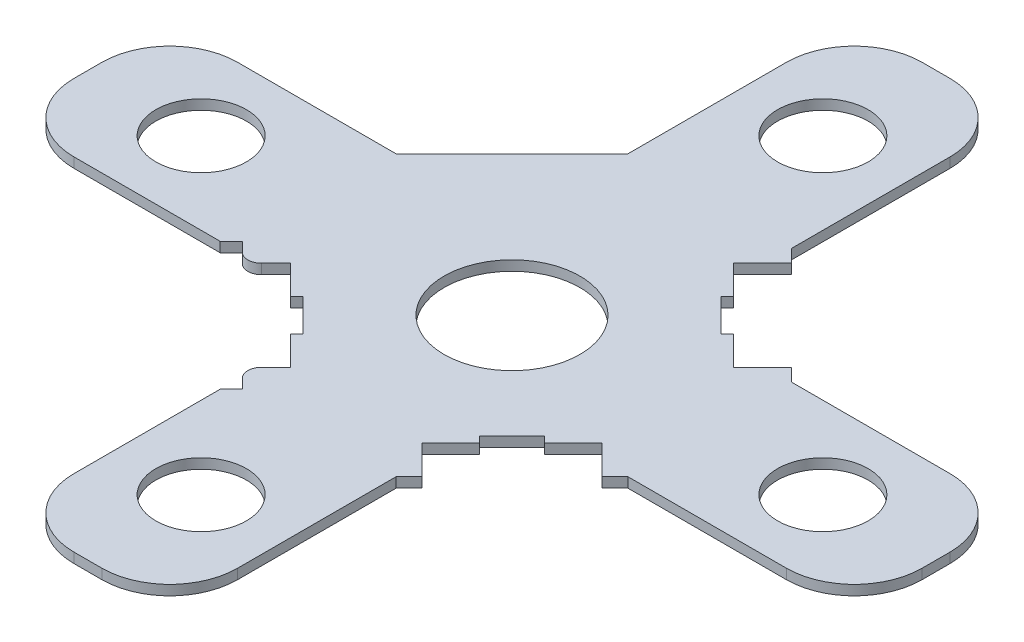
SolidWorks part; units mm, degrees
material "cardboard"
ref_plane "Front Plane" through (0, 0, 0) normal (0, 0, 1) x (1, 0, 0)
ref_plane "Top Plane" through (0, 0, 0) normal (0, 1, 0) x (1, 0, 0)
ref_plane "Right Plane" through (0, 0, 0) normal (1, 0, 0) x (0, 0, -1)
sketch "Sketch1" plane through (0, 0, 0) normal (0, 1, 0) x (1, 0, 0)
  line L0 (-130.5636, 127.4376) -> (-119.5636, 127.4376)
  line L1 (-120.5636, 123.4376) -> (-120.5636, 107.4376)
  line L2 (-60.7636, 123.4376) -> (-60.7636, 107.4376)
  line L3 (-118.1636, 107.4376) -> (-120.5636, 107.4376)
  line L4 (-131.9636, 123.4376) -> (-129.5636, 123.4376)
  line L5 (-131.9636, 123.4376) -> (-131.9636, 107.4376)
  line L6 (-131.9636, 107.4376) -> (-129.5636, 107.4376)
  line L7 (-129.5636, 123.4376) -> (-129.5636, 107.4376)
  line L8 (-118.1636, 123.4376) -> (-118.1636, 107.4376)
  line L9 (-118.1636, 123.4376) -> (-120.5636, 123.4376)
  line L10 (-58.3636, 123.4376) -> (-58.3636, 107.4376)
  line L11 (-94.9636, 127.4376) -> (-83.9636, 127.4376)
  line L12 (-60.7636, 123.4376) -> (-58.3636, 123.4376)
  line L13 (-60.7636, 107.4376) -> (-58.3636, 107.4376)
  line L14 (-49.3636, 123.4376) -> (-49.3636, 107.4376)
  line L15 (-46.9636, 123.4376) -> (-49.3636, 123.4376)
  line L16 (-46.9636, 123.4376) -> (-46.9636, 107.4376)
  line L17 (-46.9636, 107.4376) -> (-49.3636, 107.4376)
  line L18 (10.4364, 123.4376) -> (10.4364, 107.4376)
  line L19 (12.8364, 123.4376) -> (12.8364, 107.4376)
  line L20 (10.4364, 123.4376) -> (12.8364, 123.4376)
  line L21 (10.4364, 107.4376) -> (12.8364, 107.4376)
  line L22 (21.8364, 123.4376) -> (21.8364, 107.4376)
  line L23 (24.2364, 123.4376) -> (21.8364, 123.4376)
  line L24 (24.2364, 123.4376) -> (24.2364, 107.4376)
  line L25 (24.2364, 107.4376) -> (21.8364, 107.4376)
  line L26 (81.6364, 123.4376) -> (81.6364, 107.4376)
  line L27 (84.0364, 123.4376) -> (84.0364, 107.4376)
  line L28 (-59.3636, 127.4376) -> (-48.3636, 127.4376)
  line L29 (81.6364, 123.4376) -> (84.0364, 123.4376)
  line L30 (81.6364, 107.4376) -> (84.0364, 107.4376)
  line L31 (93.0364, 123.4376) -> (93.0364, 107.4376)
  line L32 (58.4364, 129.4376) -> (83.0364, 129.4376)
  line L33 (95.4364, 123.4376) -> (93.0364, 123.4376)
  line L34 (95.4364, 123.4376) -> (95.4364, 107.4376)
  line L35 (95.4364, 107.4376) -> (93.0364, 107.4376)
  line L36 (64.4935, 37.401) -> (70.9093, 30.9852)
  line L37 (84.3963, 17.4982) -> (86.3761, 19.4781)
  line L38 (64.4935, 37.401) -> (66.4734, 39.3809)
  line L39 (77.9804, 23.9141) -> (84.3963, 17.4982)
  line L40 (84.3963, -85.3527) -> (77.9804, -91.7686)
  line L41 (84.3963, -85.3527) -> (86.3761, -87.3326)
  line L42 (86.3761, -87.3326) -> (66.4734, -107.2354)
  line L43 (64.4935, -105.2555) -> (66.4734, -107.2354)
  line L44 (70.9093, -98.8396) -> (64.4935, -105.2555)
  line L45 (-38.3575, -105.2555) -> (-44.7733, -98.8396)
  line L46 (-38.3575, -105.2555) -> (-40.3374, -107.2354)
  line L47 (-40.3374, -107.2354) -> (-60.2402, -87.3326)
  line L48 (-58.2603, -85.3527) -> (-60.2402, -87.3326)
  line L49 (-51.8444, -91.7686) -> (-58.2603, -85.3527)
  line L50 (-23.7636, 127.4376) -> (-12.7636, 127.4376)
  line L51 (11.8364, 127.4376) -> (22.8364, 127.4376)
  line L52 (47.4364, 127.4376) -> (58.4364, 127.4376)
  line L53 (83.0364, 127.4376) -> (94.0364, 127.4376)
  line L54 (118.6364, 127.4376) -> (129.6364, 127.4376)
  line L55 (-35.0341, -101.9321) -> (-32.9647, -104.0015)
  line L56 (-4.6285, -75.7691) -> (-2.5591, -77.8386)
  line L57 (-54.9369, -82.0293) -> (-56.7046, -83.7971)
  line L58 (-35.0341, -101.9321) -> (-36.8019, -103.6999)
  line L59 (-30.8433, -49.5543) -> (-57.0063, -75.7172)
  line L60 (-57.0063, -79.9599) -> (-54.9369, -82.0293)
  line L61 (-2.5591, -77.8386) -> (-28.722, -104.0015)
  line L62 (-30.8433, -49.5543) -> (-28.7739, -51.6237)
  line L63 (-142.8636, 129.4376) -> (-130.5636, 129.4376)
  line L64 (-54.2479, 82.1393) -> (-54.2479, 87.1393)
  line L65 (-64.2479, 82.1393) -> (-64.2479, 87.1393)
  line L66 (-33.698, 73.6273) -> (-30.1625, 77.1628)
  line L67 (-26.627, 66.5562) -> (-23.0914, 70.0917)
  line L68 (-18.1149, 46.0063) -> (-13.1149, 46.0063)
  line L69 (-18.1149, 36.0063) -> (-13.1149, 36.0063)
  line L70 (-26.627, 15.4564) -> (-23.0914, 11.9208)
  line L71 (-33.698, 8.3853) -> (-30.1625, 4.8498)
  line L72 (-54.2479, -0.1268) -> (-54.2479, -5.1268)
  line L73 (-64.2479, -0.1268) -> (-64.2479, -5.1268)
  line L74 (-84.7978, 8.3853) -> (-88.3334, 4.8498)
  line L75 (62.9378, 35.8454) -> (69.3537, 29.4295)
  line L76 (76.4248, 22.3585) -> (82.8406, 15.9426)
  line L77 (76.4248, 22.3585) -> (77.9804, 23.9141)
  line L78 (69.3537, 29.4295) -> (70.9093, 30.9852)
  line L79 (31.1414, -77.5603) -> (33.9698, -74.7318)
  line L80 (56.701, -15.8538) -> (53.8726, -13.0254)
  line L81 (-142.8636, 129.4376) -> (-142.8636, 119.4376)
  line L82 (-5.0054, 9.7058) -> (-30.565, -15.8538)
  line L83 (-142.8636, 101.4376) -> (-127.0636, 101.4376)
  line L84 (-91.8689, 15.4564) -> (-95.4044, 11.9208)
  line L85 (-107.2636, 120.4376) -> (-107.2636, 110.4376)
  line L86 (66.4734, 39.3809) -> (86.3761, 19.4781)
  line L87 (-21.3493, -48.4417) -> (-1.4465, -68.3445)
  line L88 (-21.3493, -48.4417) -> (-24.5313, -51.6237)
  line L89 (-1.4465, -68.3445) -> (-4.6285, -71.5265)
  line L90 (-30.565, -15.8538) -> (-65.565, -15.8538)
  line L91 (-80.565, -30.8538) -> (-80.565, -37.0006)
  line L92 (-65.565, -52.0006) -> (-33.2897, -52.0006)
  line L93 (-110.5636, 106.4376) -> (-113.0636, 106.4376)
  line L94 (-139.5636, 126.4376) -> (-137.0636, 126.4376)
  line L95 (-139.5636, 126.4376) -> (-139.5636, 106.4376)
  line L96 (-139.5636, 106.4376) -> (-137.0636, 106.4376)
  line L97 (-137.0636, 126.4376) -> (-137.0636, 106.4376)
  line L98 (-113.0636, 126.4376) -> (-113.0636, 106.4376)
  line L99 (31.1414, 9.7058) -> (31.1414, 44.7058)
  line L100 (16.1414, 59.7058) -> (9.9946, 59.7058)
  line L101 (-5.0054, 44.7058) -> (-5.0054, 9.7058)
  line L102 (-110.5636, 126.4376) -> (-113.0636, 126.4376)
  line L103 (-110.5636, 126.4376) -> (-110.5636, 106.4376)
  line L104 (-123.0636, 101.4376) -> (-108.7636, 101.4376)
  line L105 (-107.2636, 120.4376) -> (-107.2636, 110.4376)
  line L106 (56.701, -52.0006) -> (91.701, -52.0006)
  line L107 (106.701, -37.0006) -> (106.701, -30.8538)
  line L108 (91.701, -15.8538) -> (56.701, -15.8538)
  line L109 (-73.1636, 101.4376) -> (-71.6636, 101.4376)
  line L110 (-71.6636, 129.4376) -> (-71.6636, 101.4376)
  line L111 (22.8364, 129.4376) -> (47.4364, 129.4376)
  line L112 (-71.6636, 129.4376) -> (-71.6636, 101.4376)
  line L113 (-71.6636, 101.4376) -> (-36.0636, 101.4376)
  line L114 (-36.0636, 129.4376) -> (-36.0636, 101.4376)
  line L115 (-5.0054, -80.2849) -> (-5.0054, -112.5603)
  line L116 (9.9946, -127.5603) -> (16.1414, -127.5603)
  line L117 (31.1414, -112.5603) -> (31.1414, -77.5603)
  line L118 (-12.7636, 129.4376) -> (11.8364, 129.4376)
  line L119 (-36.0636, 129.4376) -> (-36.0636, 101.4376)
  line L120 (-36.0636, 101.4376) -> (-0.4636, 101.4376)
  line L121 (-0.4636, 129.4376) -> (-0.4636, 101.4376)
  line L122 (-48.3636, 129.4376) -> (-23.7636, 129.4376)
  line L123 (-0.4636, 129.4376) -> (-0.4636, 101.4376)
  line L124 (53.8726, -54.8291) -> (56.701, -52.0006)
  line L125 (27.5825, -68.3445) -> (47.4853, -48.4417)
  line L126 (82.8406, -83.7971) -> (76.4248, -90.2129)
  line L127 (47.4853, -48.4417) -> (82.8406, -83.7971)
  line L128 (76.4248, -90.2129) -> (77.9804, -91.7686)
  line L129 (79.9603, -93.7485) -> (72.8892, -100.8195)
  line L130 (27.5825, -68.3445) -> (62.9378, -103.6999)
  line L131 (69.3537, -97.284) -> (70.9093, -98.8396)
  line L132 (69.3537, -97.284) -> (62.9378, -103.6999)
  line L133 (-36.8019, -103.6999) -> (-43.2177, -97.284)
  line L134 (-43.2177, -97.284) -> (-44.7733, -98.8396)
  line L135 (33.9698, 6.8774) -> (31.1414, 9.7058)
  line L136 (-100.381, 36.0063) -> (-105.381, 36.0063)
  line L137 (47.4853, -19.4127) -> (27.5825, 0.4901)
  line L138 (47.4853, -19.4127) -> (82.8406, 15.9426)
  line L139 (27.5825, 0.4901) -> (62.9378, 35.8454)
  line L140 (-46.7532, -100.8195) -> (-53.8243, -93.7485)
  line L141 (-50.2888, -90.2129) -> (-51.8444, -91.7686)
  line L142 (-50.2888, -90.2129) -> (-56.7046, -83.7971)
  line L143 (-64.2479, 82.1393) -> (-76.2858, 82.1393)
  line L144 (-76.2858, 82.1393) -> (-84.7978, 73.6273)
  line L145 (-0.4636, 101.4376) -> (35.1364, 101.4376)
  line L146 (35.1364, 129.4376) -> (35.1364, 101.4376)
  line L147 (-83.9636, 129.4376) -> (-59.3636, 129.4376)
  line L148 (35.1364, 129.4376) -> (35.1364, 101.4376)
  line L149 (35.1364, 101.4376) -> (70.7364, 101.4376)
  line L150 (70.7364, 129.4376) -> (70.7364, 101.4376)
  line L151 (-119.5636, 129.4376) -> (-108.7636, 129.4376)
  line L152 (70.7364, 129.4376) -> (70.7364, 101.4376)
  line L153 (70.7364, 101.4376) -> (106.3364, 101.4376)
  line L154 (106.3364, 129.4376) -> (106.3364, 101.4376)
  line L155 (129.6364, 129.4376) -> (141.9364, 129.4376)
  line L156 (106.3364, 129.4376) -> (106.3364, 101.4376)
  line L157 (106.3364, 101.4376) -> (141.9364, 101.4376)
  line L158 (141.9364, 129.4376) -> (141.9364, 119.4376)
  line L159 (-68.3636, 126.4376) -> (-65.8636, 126.4376)
  line L160 (-68.3636, 126.4376) -> (-68.3636, 106.4376)
  line L161 (-68.3636, 106.4376) -> (-65.8636, 106.4376)
  line L162 (-65.8636, 126.4376) -> (-65.8636, 106.4376)
  line L163 (-41.8636, 126.4376) -> (-41.8636, 106.4376)
  line L164 (-39.3636, 106.4376) -> (-41.8636, 106.4376)
  line L165 (-39.3636, 126.4376) -> (-39.3636, 106.4376)
  line L166 (-39.3636, 126.4376) -> (-41.8636, 126.4376)
  line L167 (-59.8636, 101.4376) -> (-59.8636, 97.4376)
  line L168 (-59.8636, 97.4376) -> (-47.8636, 97.4376)
  line L169 (-47.8636, 97.4376) -> (-47.8636, 101.4376)
  line L170 (2.8364, 126.4376) -> (5.3364, 126.4376)
  line L171 (2.8364, 126.4376) -> (2.8364, 106.4376)
  line L172 (2.8364, 106.4376) -> (5.3364, 106.4376)
  line L173 (5.3364, 126.4376) -> (5.3364, 106.4376)
  line L174 (29.3364, 126.4376) -> (29.3364, 106.4376)
  line L175 (31.8364, 106.4376) -> (29.3364, 106.4376)
  line L176 (31.8364, 126.4376) -> (31.8364, 106.4376)
  line L177 (31.8364, 126.4376) -> (29.3364, 126.4376)
  line L178 (11.3364, 101.4376) -> (11.3364, 97.4376)
  line L179 (11.3364, 97.4376) -> (23.3364, 97.4376)
  line L180 (23.3364, 97.4376) -> (23.3364, 101.4376)
  line L181 (74.0364, 126.4376) -> (76.5364, 126.4376)
  line L182 (74.0364, 126.4376) -> (74.0364, 106.4376)
  line L183 (74.0364, 106.4376) -> (76.5364, 106.4376)
  line L184 (76.5364, 126.4376) -> (76.5364, 106.4376)
  line L185 (100.5364, 126.4376) -> (100.5364, 106.4376)
  line L186 (103.0364, 106.4376) -> (100.5364, 106.4376)
  line L187 (103.0364, 126.4376) -> (103.0364, 106.4376)
  line L188 (103.0364, 126.4376) -> (100.5364, 126.4376)
  line L189 (82.5364, 101.4376) -> (82.5364, 97.4376)
  line L190 (82.5364, 97.4376) -> (94.5364, 97.4376)
  line L191 (94.5364, 97.4376) -> (94.5364, 101.4376)
  line L192 (-127.0636, 101.4376) -> (-127.0636, 102.4376)
  line L193 (-127.0636, 102.4376) -> (-123.0636, 102.4376)
  line L194 (-123.0636, 102.4376) -> (-123.0636, 101.4376)
  line L195 (-59.8636, 100.4376) -> (-55.8636, 100.4376)
  line L196 (-55.8636, 100.4376) -> (-55.8636, 102.4376)
  line L197 (-55.8636, 102.4376) -> (-51.8636, 102.4376)
  line L198 (-51.8636, 102.4376) -> (-51.8636, 100.4376)
  line L199 (-51.8636, 100.4376) -> (-47.8636, 100.4376)
  line L200 (11.3364, 100.4376) -> (15.3364, 100.4376)
  line L201 (15.3364, 100.4376) -> (15.3364, 102.4376)
  line L202 (15.3364, 102.4376) -> (19.3364, 102.4376)
  line L203 (28.9967, 1.9043) -> (35.3607, -4.4597)
  line L204 (35.3607, -4.4597) -> (32.5322, -7.2881)
  line L205 (32.5322, -7.2881) -> (39.7071, -14.463)
  line L206 (39.7071, -14.463) -> (42.5355, -11.6346)
  line L207 (42.5355, -11.6346) -> (48.8995, -17.9985)
  line L208 (48.8995, -49.856) -> (42.5355, -56.2199)
  line L209 (42.5355, -56.2199) -> (39.7071, -53.3915)
  line L210 (39.7071, -53.3915) -> (32.5322, -60.5663)
  line L211 (32.5322, -60.5663) -> (35.3607, -63.3948)
  line L212 (35.3607, -63.3948) -> (28.9967, -69.7587)
  line L213 (-2.8607, -69.7587) -> (-9.2247, -63.3948)
  line L214 (-9.2247, -63.3948) -> (-6.3963, -60.5663)
  line L215 (-6.3963, -60.5663) -> (-13.5711, -53.3915)
  line L216 (-13.5711, -53.3915) -> (-16.3995, -56.2199)
  line L217 (-16.3995, -56.2199) -> (-22.7635, -49.856)
  line L218 (-88.3334, 77.1628) -> (-95.4044, 70.0917)
  line L219 (-91.8689, 66.5562) -> (-100.381, 58.0441)
  line L220 (-100.381, 58.0441) -> (-100.381, 46.0063)
  line L221 (-105.381, 46.0063) -> (-105.381, 36.0063)
  line L222 (-100.381, 36.0063) -> (-100.381, 23.9684)
  line L223 (-100.381, 23.9684) -> (-91.8689, 15.4564)
  line L224 (-95.4044, 11.9208) -> (-88.3334, 4.8498)
  line L225 (-84.7978, 8.3853) -> (-76.2858, -0.1268)
  line L226 (-76.2858, -0.1268) -> (-64.2479, -0.1268)
  line L227 (-64.2479, -5.1268) -> (-54.2479, -5.1268)
  line L228 (-54.2479, -0.1268) -> (-42.2101, -0.1268)
  line L229 (-42.2101, -0.1268) -> (-33.698, 8.3853)
  line L230 (-30.1625, 4.8498) -> (-23.0914, 11.9208)
  line L231 (-26.627, 15.4564) -> (-18.1149, 23.9684)
  line L232 (-18.1149, 23.9684) -> (-18.1149, 36.0063)
  line L233 (-13.1149, 36.0063) -> (-13.1149, 46.0063)
  line L234 (-18.1149, 46.0063) -> (-18.1149, 58.0441)
  line L235 (-18.1149, 58.0441) -> (-26.627, 66.5562)
  line L236 (-23.0914, 70.0917) -> (-30.1625, 77.1628)
  line L237 (-33.698, 73.6273) -> (-42.2101, 82.1393)
  line L238 (-42.2101, 82.1393) -> (-54.2479, 82.1393)
  line L239 (-54.2479, 87.1393) -> (-64.2479, 87.1393)
  line L240 (-100.381, 46.0063) -> (-105.381, 46.0063)
  line L241 (-91.8689, 66.5562) -> (-95.4044, 70.0917)
  line L242 (-84.7978, 73.6273) -> (-88.3334, 77.1628)
  line L243 (19.3364, 102.4376) -> (19.3364, 100.4376)
  line L244 (19.3364, 100.4376) -> (23.3364, 100.4376)
  line L245 (82.5364, 100.4376) -> (86.5364, 100.4376)
  line L246 (86.5364, 100.4376) -> (86.5364, 102.4376)
  line L247 (86.5364, 102.4376) -> (90.5364, 102.4376)
  line L248 (90.5364, 102.4376) -> (90.5364, 100.4376)
  line L249 (90.5364, 100.4376) -> (94.5364, 100.4376)
  line L250 (141.9364, 119.4376) -> (143.9364, 119.4376)
  line L251 (143.9364, 111.4376) -> (141.9364, 111.4376)
  line L252 (141.9364, 111.4376) -> (141.9364, 101.4376)
  line L253 (-142.8636, 119.4376) -> (-141.8636, 119.4376)
  line L254 (-141.8636, 119.4376) -> (-141.8636, 111.4376)
  line L255 (-141.8636, 111.4376) -> (-142.8636, 111.4376)
  line L256 (-142.8636, 111.4376) -> (-142.8636, 101.4376)
  line L257 (-108.7636, 129.4376) -> (-108.7636, 120.4376)
  line L258 (-108.7636, 120.4376) -> (-107.2636, 120.4376)
  line L259 (-107.2636, 110.4376) -> (-108.7636, 110.4376)
  line L260 (-108.7636, 110.4376) -> (-108.7636, 101.4376)
  line L261 (-73.1636, 129.4376) -> (-73.1636, 120.4376)
  line L262 (-73.1636, 120.4376) -> (-70.1636, 120.4376)
  line L263 (-70.1636, 120.4376) -> (-70.1636, 110.4376)
  line L264 (-70.1636, 110.4376) -> (-73.1636, 110.4376)
  line L265 (-73.1636, 110.4376) -> (-73.1636, 101.4376)
  line L266 (-37.5636, 129.4376) -> (-37.5636, 120.4376)
  line L267 (-37.5636, 120.4376) -> (-34.5636, 120.4376)
  line L268 (-34.5636, 120.4376) -> (-34.5636, 110.4376)
  line L269 (-34.5636, 110.4376) -> (-37.5636, 110.4376)
  line L270 (-37.5636, 110.4376) -> (-37.5636, 101.4376)
  line L271 (-1.9636, 129.4376) -> (-1.9636, 120.4376)
  line L272 (-1.9636, 120.4376) -> (1.0364, 120.4376)
  line L273 (1.0364, 120.4376) -> (1.0364, 110.4376)
  line L274 (1.0364, 110.4376) -> (-1.9636, 110.4376)
  line L275 (-1.9636, 110.4376) -> (-1.9636, 101.4376)
  line L276 (33.6364, 129.4376) -> (33.6364, 120.4376)
  line L277 (33.6364, 120.4376) -> (36.6364, 120.4376)
  line L278 (36.6364, 120.4376) -> (36.6364, 110.4376)
  line L279 (36.6364, 110.4376) -> (33.6364, 110.4376)
  line L280 (33.6364, 110.4376) -> (33.6364, 101.4376)
  line L281 (69.2364, 129.4376) -> (69.2364, 120.4376)
  line L282 (69.2364, 120.4376) -> (72.2364, 120.4376)
  line L283 (72.2364, 120.4376) -> (72.2364, 110.4376)
  line L284 (72.2364, 110.4376) -> (69.2364, 110.4376)
  line L285 (69.2364, 110.4376) -> (69.2364, 101.4376)
  line L286 (104.8364, 129.4376) -> (104.8364, 120.4376)
  line L287 (104.8364, 120.4376) -> (107.8364, 120.4376)
  line L288 (107.8364, 120.4376) -> (107.8364, 110.4376)
  line L289 (107.8364, 110.4376) -> (104.8364, 110.4376)
  line L290 (104.8364, 110.4376) -> (104.8364, 101.4376)
  line L291 (143.9364, 119.4376) -> (143.9364, 111.4376)
  line L292 (-130.5636, 129.4376) -> (-130.5636, 127.4376)
  line L293 (-119.5636, 129.4376) -> (-119.5636, 127.4376)
  line L294 (-94.9636, 129.4376) -> (-94.9636, 127.4376)
  line L295 (-83.9636, 129.4376) -> (-83.9636, 127.4376)
  line L296 (-59.3636, 129.4376) -> (-59.3636, 127.4376)
  line L297 (-48.3636, 129.4376) -> (-48.3636, 127.4376)
  line L298 (-23.7636, 129.4376) -> (-23.7636, 127.4376)
  line L299 (-12.7636, 129.4376) -> (-12.7636, 127.4376)
  line L300 (11.8364, 129.4376) -> (11.8364, 127.4376)
  line L301 (22.8364, 129.4376) -> (22.8364, 127.4376)
  line L302 (47.4364, 129.4376) -> (47.4364, 127.4376)
  line L303 (58.4364, 129.4376) -> (58.4364, 127.4376)
  line L304 (83.0364, 129.4376) -> (83.0364, 127.4376)
  line L305 (94.0364, 129.4376) -> (94.0364, 127.4376)
  line L306 (118.6364, 129.4376) -> (118.6364, 127.4376)
  line L307 (129.6364, 129.4376) -> (129.6364, 127.4376)
  line L308 (94.0364, 129.4376) -> (118.6364, 129.4376)
  circle A0 centre (-30.8433, -56.6254) radius 1.75
  circle A1 centre (-59.2479, 68.0063) radius 6
  circle A2 centre (-40.156, 60.0982) radius 6
  circle A3 centre (-32.2479, 41.0063) radius 6
  circle A4 centre (-9.6301, -77.8386) radius 1.75
  circle A5 centre (-30.8433, -99.0518) radius 1.75
  circle A6 centre (13.068, 34.7058) radius 10
  circle A7 centre (-125.0636, 113.9376) radius 1
  circle A8 centre (-52.0565, -77.8386) radius 1.75
  arc A9 (-28.7739, -51.6237) -> (-24.5313, -51.6237) centre (-26.6526, -49.5024) ccw
  arc A10 (-4.6285, -75.7691) -> (-4.6285, -71.5265) centre (-2.5072, -73.6478) cw
  circle A11 centre (-53.8636, 113.9376) radius 1
  circle A12 centre (81.701, -33.9272) radius 10
  circle A13 centre (13.068, -33.9272) radius 15
  arc A14 (-65.565, -15.8538) -> (-80.565, -30.8538) centre (-65.565, -30.8538) ccw
  arc A15 (-80.565, -37.0006) -> (-65.565, -52.0006) centre (-65.565, -37.0006) ccw
  arc A16 (-5.0054, -112.5603) -> (9.9946, -127.5603) centre (9.9946, -112.5603) ccw
  arc A17 (16.1414, -127.5603) -> (31.1414, -112.5603) centre (16.1414, -112.5603) ccw
  arc A18 (91.701, -52.0006) -> (106.701, -37.0006) centre (91.701, -37.0006) ccw
  arc A19 (106.701, -30.8538) -> (91.701, -15.8538) centre (91.701, -30.8538) ccw
  arc A20 (31.1414, 44.7058) -> (16.1414, 59.7058) centre (16.1414, 44.7058) ccw
  circle A21 centre (17.3364, 113.9376) radius 1
  circle A22 centre (13.068, -102.5603) radius 10
  circle A23 centre (88.5364, 113.9376) radius 1
  circle A24 centre (-55.565, -33.9272) radius 10
  circle A25 centre (-40.156, 21.9144) radius 6
  circle A26 centre (-89.4636, 115.4376) radius 7.5
  circle A27 centre (-18.2636, 115.4376) radius 7.5
  circle A28 centre (52.9364, 115.4376) radius 7.5
  circle A29 centre (124.1364, 115.4376) radius 7.5
  arc A30 (9.9946, 59.7058) -> (-5.0054, 44.7058) centre (9.9946, 44.7058) ccw
  arc A31 (-32.9647, -104.0015) -> (-28.722, -104.0015) centre (-30.8433, -101.8802) ccw
  arc A32 (-57.0063, -75.7172) -> (-57.0063, -79.9599) centre (-54.885, -77.8386) ccw
  circle A33 centre (-59.2479, 14.0063) radius 6
  circle A34 centre (-78.3398, 21.9144) radius 6
  circle A35 centre (-86.2479, 41.0063) radius 6
  circle A36 centre (-78.3398, 60.0982) radius 6
  circle A37 centre (-59.2479, 41.0063) radius 15
  point P67 (13.068, -33.9272)
  point P113 (13.068, -33.9272)
  point P166 (13.068, -33.9272)
  point P168 (13.068, -33.9272)
  point P177 (13.068, -33.9272)
  point P182 (13.068, -33.9272)
  point P246 (13.068, -33.9272)
  point P268 (13.068, -33.9272)
  point P279 (13.068, -33.9272)
  point P313 (-59.2479, 41.0063)
  point P314 (-59.2479, 41.0063)
  point P399 (-59.2479, 41.0063)
extrude "Boss-Extrude1" add sketch "Sketch1" along normal blind 2.2 contours L100 A30 L101 L82 L90 A14 L91 A15 L92 L59 L62 A9 L88 L87 L216 L215 L214 L89 A10 L56 L61 L115 A16 L116 A17 L117 L79 L130 L125 L211 L210 L209 L127 L124 L106 A18 L107 A19 L108 L80 L138 L137 L206 L205
